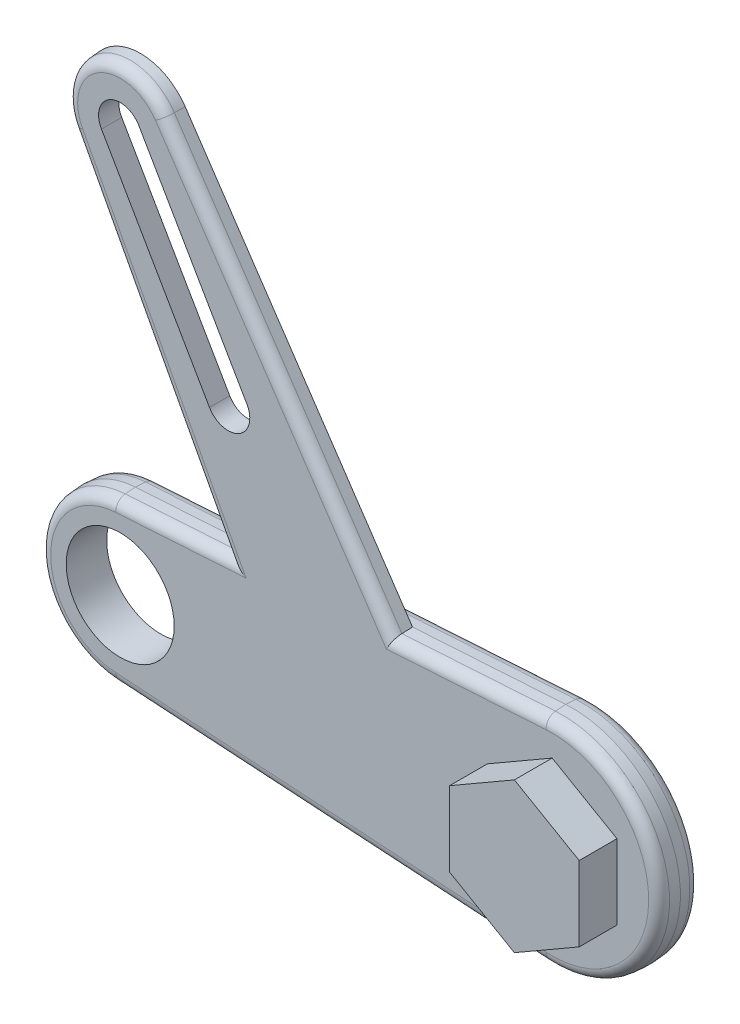
SolidWorks part; units mm, degrees
ref_plane "Спереди" through (0, 0, 0) normal (0, 0, 1) x (1, 0, 0)
ref_plane "Сверху" through (0, 0, 0) normal (0, 1, 0) x (1, 0, 0)
ref_plane "Справа" through (0, 0, 0) normal (1, 0, 0) x (0, 0, -1)
sketch "Эскиз1" plane through (0, 0, 0) normal (0, 0, 1) x (1, 0, 0)
  line L0 (-18.8114, 0) -> (106.0792, 0) construction
  line L1 (-0.9375, 14.9707) -> (78.75, 19.9609)
  line L2 (-0.9375, -14.9707) -> (78.75, -19.9609)
  arc A0 (78.75, 19.9609) -> (78.75, -19.9609) centre (80, 0) cw
  arc A1 (-0.9375, 14.9707) -> (-0.9375, -14.9707) centre (0, 0) ccw
  dimension "D1" = 15
  dimension "D2" = 20
  dimension "D3" = 80
extrude "основание" add sketch "Эскиз1" along normal mid plane 7.5 draft 4 contours L1 A0 L2 A1
sketch "Эскиз2" plane through (0, 0, 0) normal (0, 0, 1) x (1, 0, 0)
  line L0 (-17.7804, 0) -> (109.1115, 0) construction
  line L1 (43.3013, 0) -> (0, 75) construction
  line L2 (-8.8295, 70.3053) -> (28.5525, 0)
  line L3 (8.2904, 80.5919) -> (62.6503, 0)
  line L4 (28.5525, 0) -> (62.6503, 0)
  arc A0 (8.2904, 80.5919) -> (-8.8295, 70.3053) centre (0, 75) ccw
  dimension "D2" = 10
  dimension "D1" = 120
  dimension "D3" = 75
  dimension "D4" = 4
  dimension "D5" = 2
extrude "ручка с прорезью" add sketch "Эскиз2" along direction (0, 0, 1) on the side of the normal up to surface (3.75 mm away) draft 4
sketch "Эскиз3" plane through (0, 0, 3.75) normal (0, 0, 1) x (1, 0, 0)
  line L1 (0, 75) -> (43.3013, 0) construction
  line L2 (0, 75) -> (20, 40.359) construction
  line L3 (3.4641, 77) -> (23.4641, 42.359)
  line L4 (-3.4641, 73) -> (16.5359, 38.359)
  line L5 (-18.8114, 0) -> (106.0792, 0) construction
  arc A0 (3.4641, 77) -> (-3.4641, 73) centre (0, 75) ccw
  arc A1 (16.5359, 38.359) -> (23.4641, 42.359) centre (20, 40.359) ccw
  point P2 (10, 57.6795)
  dimension "D1" = 4
  dimension "D2" = 40
  dimension "D3" = 120
extrude "прорезь" cut sketch "Эскиз3" against normal blind 10 contours L3 A1 L4 A0
sketch "Эскиз4" plane through (0, 0, 3.75) normal (0, 0, 1) x (1, 0, 0)
  circle A0 centre (0, 0) radius 10
  dimension "D1" = 20
extrude "отверстие1" cut sketch "Эскиз4" against normal blind 10
sketch "Эскиз5" plane through (0, 0, 3.75) normal (0, 0, 1) x (1, 0, 0)
  line L1 (80, 13.8564) -> (68, 6.9282)
  line L2 (68, 6.9282) -> (68, -6.9282)
  line L3 (68, -6.9282) -> (80, -13.8564)
  line L4 (80, -13.8564) -> (92, -6.9282)
  line L5 (92, -6.9282) -> (92, 6.9282)
  line L6 (92, 6.9282) -> (80, 13.8564)
  circle A0 centre (80, 0) radius 13.8564 construction
  arc A1 (78.7664, -19.6992) -> (78.7664, 19.6992) centre (80, 0) ccw construction
  dimension "D1" = 24
extrude "Шестигранник" add sketch "Эскиз5" along normal blind 7
fillet "Скругление2" radius 2 9 edges at (99.7378, 0, -3.75) (99.7378, 0, 3.75) (9.7001, 15.3741, 3.75) (-14.7378, 0, 3.75) (38.9226, -17.2041, 3.75) (38.9226, 17.2041, -3.75) (64.5088, 18.8063, 3.75) (-14.7378, 0, -3.75) (38.9226, -17.2041, -3.75)
fillet "Скругление3" radius 2 3 edges at (6.3425, 42.3296, 3.75) (-5.0153, 83.3469, 3.75) (29.7668, 48.2829, 3.75)
